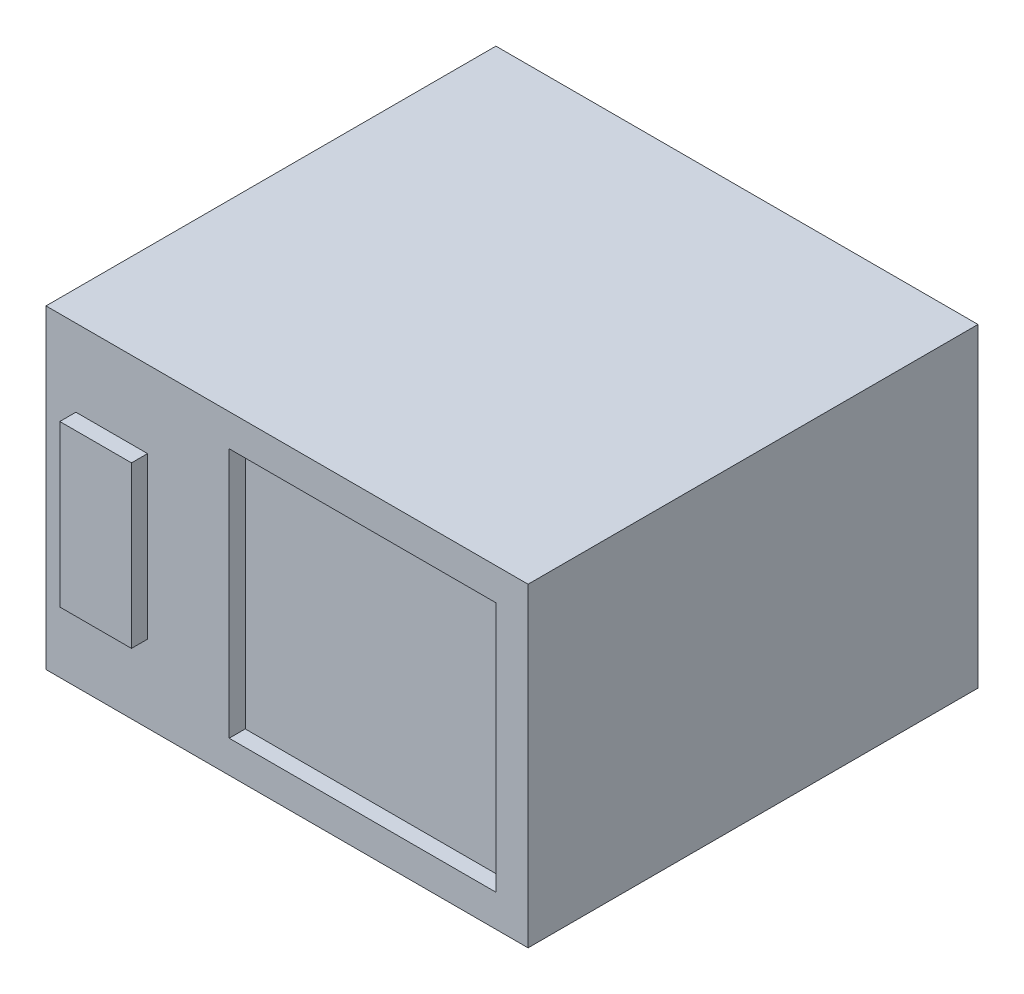
SolidWorks part; units mm, degrees
ref_plane "Front Plane" through (0, 0, 0) normal (0, 0, 1) x (1, 0, 0)
ref_plane "Top Plane" through (0, 0, 0) normal (0, 1, 0) x (1, 0, 0)
ref_plane "Right Plane" through (0, 0, 0) normal (1, 0, 0) x (0, 0, -1)
sketch "Sketch1" plane through (0, 0, 0) normal (0, 1, 0) x (1, 0, 0)
  line L1 (-75, -70) -> (75, -70)
  line L2 (-75, -70) -> (-75, 70)
  line L3 (-75, 70) -> (75, 70)
  line L4 (75, -70) -> (75, 70)
  line L5 (-75, -70) -> (75, 70) construction
  line L6 (-75, 70) -> (75, -70) construction
  point P0 (0, 0)
  dimension "D1" = 150
  dimension "D2" = 140
extrude "Boss-Extrude1" add sketch "Sketch1" along normal mid plane 98
sketch "Sketch2" plane through (0, 0, 70) normal (0, 0, 1) x (1, 0, 0)
  line L0 (75, 49) -> (75, -49) construction
  line L1 (-18, 39) -> (65, 39)
  line L2 (-18, 39) -> (-18, -39)
  line L3 (-18, -39) -> (65, -39)
  line L4 (65, 39) -> (65, -39)
  point P4 (-18, 0)
  dimension "D1" = 83
  dimension "D2" = 78
  dimension "D3" = 10
extrude "Cut-Extrude1" cut sketch "Sketch2" against normal blind 5
sketch "Sketch3" plane through (0, 0, 70) normal (0, 0, 1) x (1, 0, 0)
  line L0 (-75, 49) -> (-75, -49) construction
  line L1 (-65.7, 25) -> (-43.4, 25)
  line L2 (-65.7, 25) -> (-65.7, -25)
  line L3 (-65.7, -25) -> (-43.4, -25)
  line L4 (-43.4, 25) -> (-43.4, -25)
  point P6 (-43.4, 0)
  dimension "D1" = 22.3
  dimension "D2" = 50
  dimension "D3" = 9.3
extrude "Boss-Extrude2" add sketch "Sketch3" along normal blind 5
sketch "Sketch4" plane through (0, 0, -70) normal (0, 0, -1) x (-1, 0, 0)
  line L0 (75, 49) -> (75, -49) construction
  line L1 (-24, 39.5) -> (60, 39.5)
  line L2 (-24, 39.5) -> (-24, -39.5)
  line L3 (-24, -39.5) -> (60, -39.5)
  line L4 (60, 39.5) -> (60, -39.5)
  point P4 (-24, 0)
  dimension "D1" = 84
  dimension "D2" = 79
  dimension "D3" = 15
extrude "Cut-Extrude2" cut sketch "Sketch4" against normal blind 5
